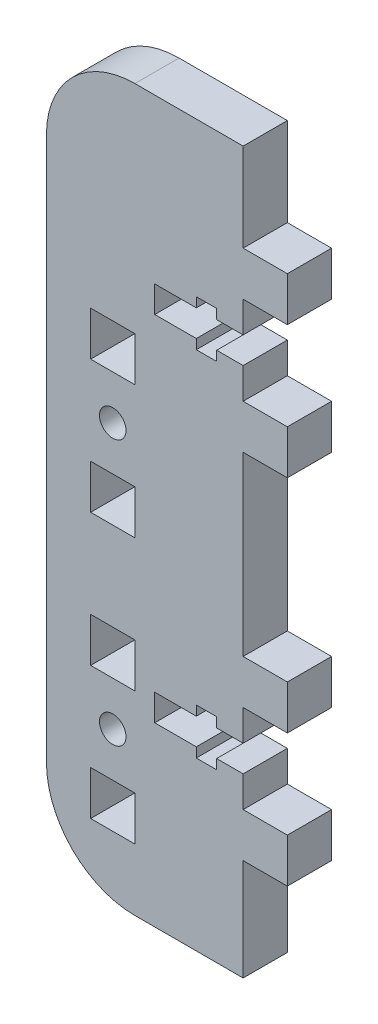
SolidWorks part; units mm, degrees
ref_plane "Front Plane" through (0, 0, 0) normal (0, 0, 1) x (1, 0, 0)
ref_plane "Top Plane" through (0, 0, 0) normal (0, 1, 0) x (1, 0, 0)
ref_plane "Right Plane" through (0, 0, 0) normal (1, 0, 0) x (0, 0, -1)
sketch "Sketch1" plane through (0, 0, 0) normal (0, 0, 1) x (1, 0, 0)
  line L0 (22.25, 81.5) -> (22.25, 71.5)
  line L1 (0, 0) -> (22.25, 0) construction
  line L3 (0, 81.5) -> (22.25, 81.5) construction
  line L4 (22.25, 0) -> (22.25, 81.5) construction
  line L5 (22.25, 51.5) -> (22.25, 31.5)
  line L6 (22.25, 11.5) -> (22.25, 0)
  line L7 (22.25, 61.5) -> (54.8334, 61.5) construction
  line L8 (22.25, 60) -> (22.25, 56.5)
  line L9 (27.25, 56.5) -> (27.25, 51.5)
  line L10 (27.25, 51.5) -> (22.25, 51.5)
  line L11 (27.25, 56.5) -> (22.25, 56.5)
  line L12 (22.25, 63) -> (22.25, 66.5)
  line L13 (22.25, 66.5) -> (27.25, 66.5)
  line L14 (27.25, 66.5) -> (27.25, 71.5)
  line L15 (27.25, 71.5) -> (22.25, 71.5)
  line L16 (22.25, 21.5) -> (54.8334, 21.5) construction
  line L17 (22.25, 20) -> (22.25, 16.5)
  line L18 (27.25, 16.5) -> (27.25, 11.5)
  line L19 (27.25, 11.5) -> (22.25, 11.5)
  line L20 (27.25, 16.5) -> (22.25, 16.5)
  line L21 (22.25, 23) -> (22.25, 26.5)
  line L22 (22.25, 26.5) -> (27.25, 26.5)
  line L23 (27.25, 26.5) -> (27.25, 31.5)
  line L24 (27.25, 31.5) -> (22.25, 31.5)
  line L25 (22.25, 60) -> (22.25, 63) construction
  line L26 (22.25, 63) -> (19.25, 63)
  line L27 (16.95, 63) -> (16.95, 64.1)
  line L28 (19.25, 58.9) -> (16.95, 58.9)
  line L29 (19.25, 64.1) -> (19.25, 63)
  line L30 (16.95, 63) -> (12.25, 63)
  line L31 (12.25, 63) -> (12.25, 60)
  line L32 (12.25, 60) -> (16.95, 60)
  line L33 (19.25, 60) -> (19.25, 58.9)
  line L34 (16.95, 64.1) -> (19.25, 64.1)
  line L35 (16.95, 58.9) -> (16.95, 60)
  line L36 (19.25, 60) -> (22.25, 60)
  line L37 (12.25, 61.5) -> (22.25, 61.5) construction
  line L38 (22.25, 20) -> (22.25, 23) construction
  line L39 (22.25, 23) -> (19.25, 23)
  line L40 (16.95, 23) -> (16.95, 24.1)
  line L41 (19.25, 18.9) -> (16.95, 18.9)
  line L42 (19.25, 24.1) -> (19.25, 23)
  line L43 (16.95, 23) -> (12.25, 23)
  line L44 (12.25, 23) -> (12.25, 20)
  line L45 (12.25, 20) -> (16.95, 20)
  line L46 (19.25, 20) -> (19.25, 18.9)
  line L47 (16.95, 24.1) -> (19.25, 24.1)
  line L48 (16.95, 18.9) -> (16.95, 20)
  line L49 (19.25, 20) -> (22.25, 20)
  line L50 (12.25, 21.5) -> (22.25, 21.5) construction
  line L51 (10, 94.8027) -> (10, 0) construction
  line L55 (0, 0) -> (0, 81.5)
  line L64 (0, 81.5) -> (22.25, 81.5)
  line L102 (0, 0) -> (22.25, 0)
  point P11 (24.75, 31.5)
  line B0 (5, 42) -> (5, 37)
  line B1 (5, 42) -> (10, 42)
  line B2 (10, 42) -> (10, 37)
  line B3 (5, 37) -> (10, 37)
  line B4 (5, 52) -> (5, 57)
  line B5 (5, 52) -> (10, 52)
  line B6 (10, 52) -> (10, 57)
  line B7 (5, 57) -> (10, 57)
  circle B8 centre (7.5, 47) radius 1.5
  line B9 (5, 12) -> (5, 7)
  line B10 (5, 12) -> (10, 12)
  line B11 (10, 12) -> (10, 7)
  line B12 (5, 7) -> (10, 7)
  line B13 (5, 22) -> (5, 27)
  line B14 (5, 22) -> (10, 22)
  line B15 (10, 22) -> (10, 27)
  line B16 (5, 27) -> (10, 27)
  circle B17 centre (7.5, 17) radius 1.5
  dimension "D2" = 20
  dimension "D3" = 5
  dimension "D4" = 7
  dimension "D5" = 10
  dimension "D6" = 5
  dimension "D7" = 5
  dimension "D8" = 10
  dimension "D9" = 5
  dimension "D10" = 5
  dimension "D11" = 5.2
  dimension "D12" = 3
  dimension "D13" = 2.3
  dimension "D14" = 3
  dimension "D15" = 10
  dimension "D16" = 5.2
  dimension "D17" = 3
  dimension "D18" = 2.3
  dimension "D19" = 3
  dimension "D20" = 10
  dimension "D21" = 12.25
  dimension "D22" = 24.5
  dimension "D23" = 10
  dimension "D24" = 11.5
sketch_block_instance "Trou M3 plots 5mm-1"
sketch_block "Trou M3 plots 5mm" parameters "D2"=3, "D1"=5, "D3"=5, "D4"=10
sketch_block_instance "Trou M3 plots 5mm-2"
extrude "Boss-Extrude1" add sketch "Sketch1" along normal blind 5
fillet "Congé1" radius 10 2 edges at (0, 0, 2.5) (0, 81.5, 2.5)
